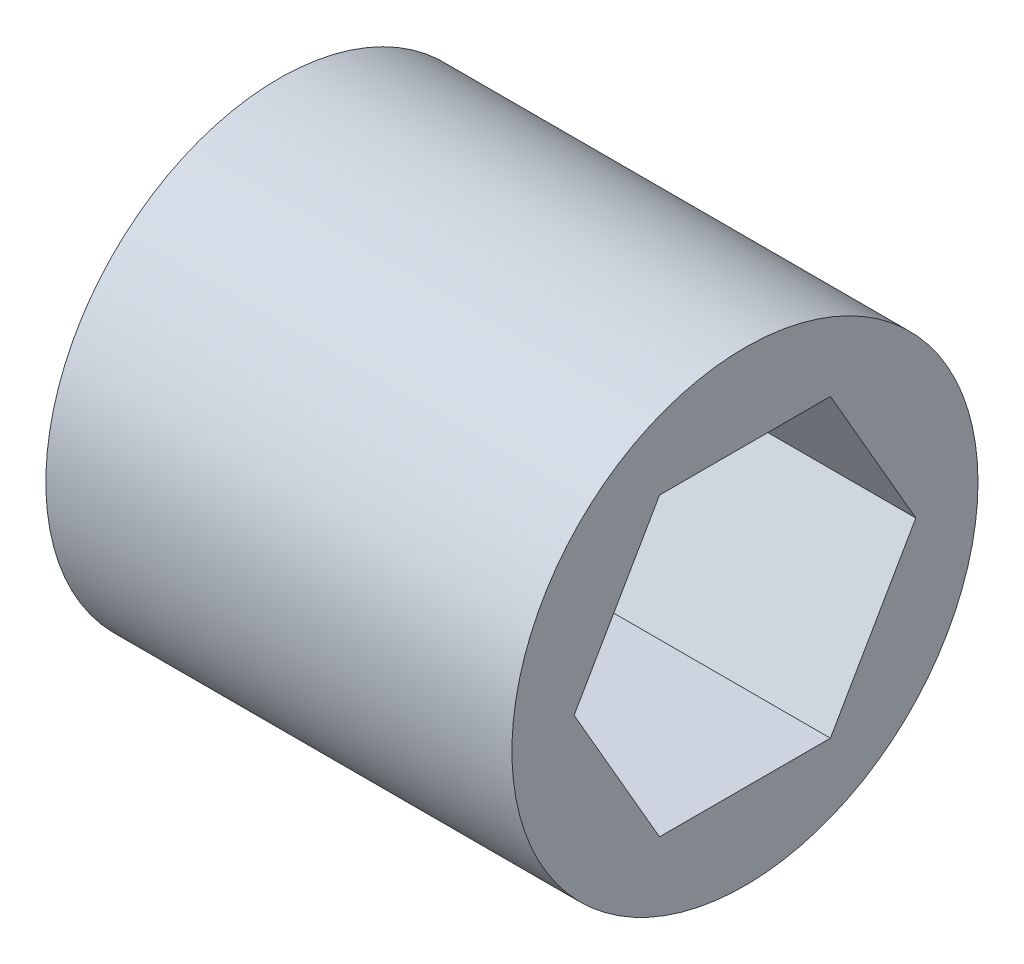
SolidWorks part; units mm, degrees
ref_plane "Alzado" through (0, 0, 0) normal (0, 0, 1) x (1, 0, 0)
ref_plane "Planta" through (0, 0, 0) normal (0, 1, 0) x (1, 0, 0)
ref_plane "Vista lateral" through (0, 0, 0) normal (1, 0, 0) x (0, 0, -1)
sketch "Croquis1" plane through (0, 0, 0) normal (1, 0, 0) x (0, 0, -1)
  line L1 (7.3323, 0) -> (3.6662, 6.35)
  line L2 (3.6662, 6.35) -> (-3.6662, 6.35)
  line L3 (-3.6662, 6.35) -> (-7.3323, 0)
  line L4 (-7.3323, 0) -> (-3.6662, -6.35)
  line L5 (-3.6662, -6.35) -> (3.6662, -6.35)
  line L6 (3.6662, -6.35) -> (7.3323, 0)
  circle A0 centre (0, 0) radius 10
  circle A1 centre (0, 0) radius 6.35 construction
  dimension "D1" = 20
extrude "Saliente-Extruir1" add sketch "Croquis1" along normal blind 20
